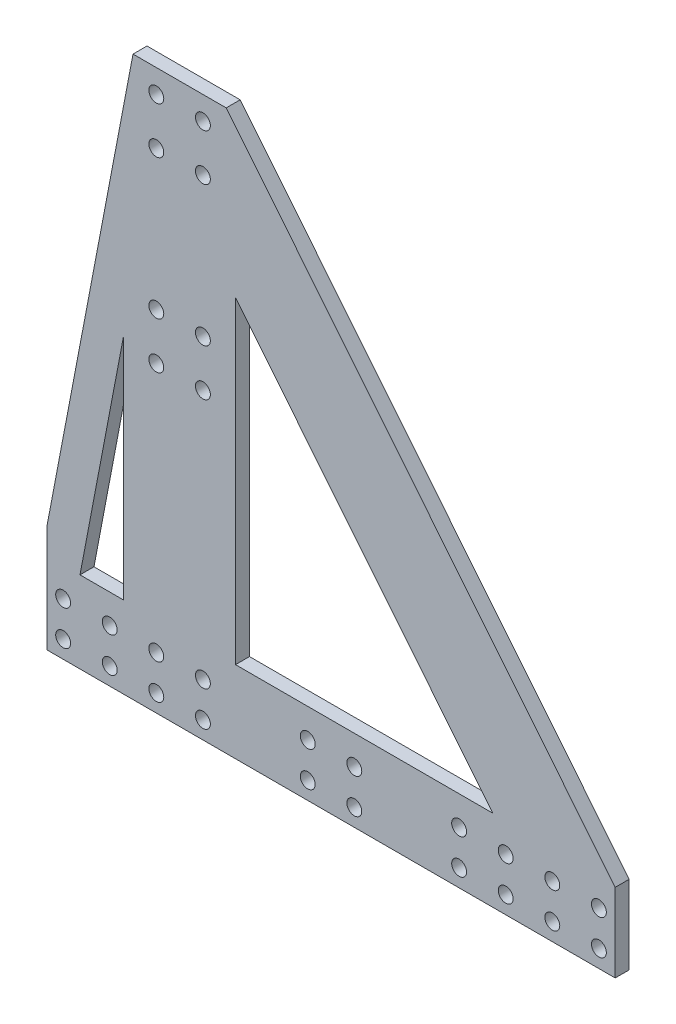
SolidWorks part; units mm, degrees
ref_plane "前视基准面" through (0, 0, 0) normal (0, 0, 1) x (1, 0, 0)
ref_plane "上视基准面" through (0, 0, 0) normal (0, 1, 0) x (1, 0, 0)
ref_plane "右视基准面" through (0, 0, 0) normal (1, 0, 0) x (0, 0, -1)
other "Configuration Table"
sketch "草图1" plane through (0, 0, 0) normal (0, 0, 1) x (1, 0, 0)
  line L0 (0, 0) -> (20, 0)
  line L1 (20, 0) -> (105, -105)
  line L2 (105, -105) -> (105, -120)
  line L3 (105, -120) -> (-20, -120)
  line L4 (-20, -120) -> (-20, -105)
  line L5 (-20, -105) -> (0, 0)
  line L6 (10, 0) -> (10, -120) construction
  dimension "D1" = 15
  dimension "D2" = 20
  dimension "D3" = 15
  dimension "D4" = 120
  dimension "D5" = 125
  dimension "D6" = 30
extrude "凸台-拉伸1" add sketch "草图1" along normal blind 3
sketch "草图2" plane through (0, 0, 3) normal (0, 0, 1) x (1, 0, 0)
  line L0 (10, 0) -> (10, -120) construction
  line L1 (20, 0) -> (0, 0) construction
  line L2 (-20, -120) -> (105, -120) construction
  line L3 (10, -10) -> (-19.8035, -10) construction
  line L4 (-20, -112.5) -> (105, -112.5) construction
  line L5 (-20, -105) -> (-20, -120) construction
  line L6 (105, -120) -> (105, -105) construction
  line L7 (-10, -112.5) -> (-10, -120) construction
  line L8 (42.5, -120) -> (42.5, -112.5) construction
  line L9 (95, -112.5) -> (95, -120) construction
  line L10 (-2, -53.2551) -> (-2, -102.5)
  line L11 (-2, -102.5) -> (-11.38, -102.5)
  line L12 (-11.38, -102.5) -> (-2, -53.2551)
  line L13 (0, 0) -> (-20, -105) construction
  line L17 (105, -120) -> (105, -80)
  line L18 (-18.5, -120) -> (-20, -120)
  line L19 (-18.5, -120) -> (-18.5, -80)
  line L20 (-18.5, -80) -> (-20, -80)
  line L21 (-20, -120) -> (-20, -80)
  line L22 (103.5, -80) -> (105, -80)
  line L23 (103.5, -120) -> (103.5, -80)
  line L24 (103.5, -120) -> (105, -120)
  line L25 (10, -30) -> (-38.6049, -30) construction
  line L26 (22, -34.2571) -> (22, -102.5)
  line L27 (22, -102.5) -> (77.2443, -102.5)
  line L28 (77.2443, -102.5) -> (22, -34.2571)
  line L29 (105, -105) -> (20, 0) construction
  line L30 (0, -120) -> (0, -112.5) construction
  circle A0 centre (5, -5) radius 1.6
  circle A1 centre (15, -5) radius 1.6
  circle A2 centre (15, -15) radius 1.6
  circle A3 centre (5, -15) radius 1.6
  circle A4 centre (-15, -116.25) radius 1.6
  circle A5 centre (-15, -108.75) radius 1.6
  circle A6 centre (-5, -116.25) radius 1.6
  circle A7 centre (-5, -108.75) radius 1.6
  circle A8 centre (90, -108.75) radius 1.6
  circle A9 centre (90, -116.25) radius 1.6
  circle A10 centre (100, -108.75) radius 1.6
  circle A11 centre (100, -116.25) radius 1.6
  circle A12 centre (37.5, -116.25) radius 1.6
  circle A13 centre (47.5, -116.25) radius 1.6
  circle A14 centre (47.5, -108.75) radius 1.6
  circle A15 centre (37.5, -108.75) radius 1.6
  circle A16 centre (5, -45) radius 1.6
  circle A17 centre (15, -45) radius 1.6
  circle A18 centre (15, -55) radius 1.6
  circle A19 centre (5, -55) radius 1.6
  circle A20 centre (5, -108.75) radius 1.6
  circle A21 centre (5, -116.25) radius 1.6
  circle A22 centre (15, -116.25) radius 1.6
  circle A23 centre (15, -108.75) radius 1.6
  circle A24 centre (70, -116.25) radius 1.6
  circle A25 centre (80, -116.25) radius 1.6
  circle A26 centre (70, -108.75) radius 1.6
  circle A27 centre (80, -108.75) radius 1.6
  dimension "D1" = 10
  dimension "D3" = 3.2
  dimension "D5" = 5
  dimension "D7" = 3.2
  dimension "D12" = 3.2
  dimension "D2" = 5
  dimension "D4" = 5
  dimension "D6" = 10
  dimension "D8" = 3.75
  dimension "D9" = 12
  dimension "D10" = 10
  dimension "D11" = 8
  dimension "D13" = 5
  dimension "D14" = 3.75
  dimension "D15" = 1.5
  dimension "D16" = 40
  dimension "D17" = 20
  dimension "D18" = 12
  dimension "D19" = 10
  dimension "D20" = 20
  dimension "D21" = 10
extrude "切除-拉伸1" cut sketch "草图2" against normal through all
